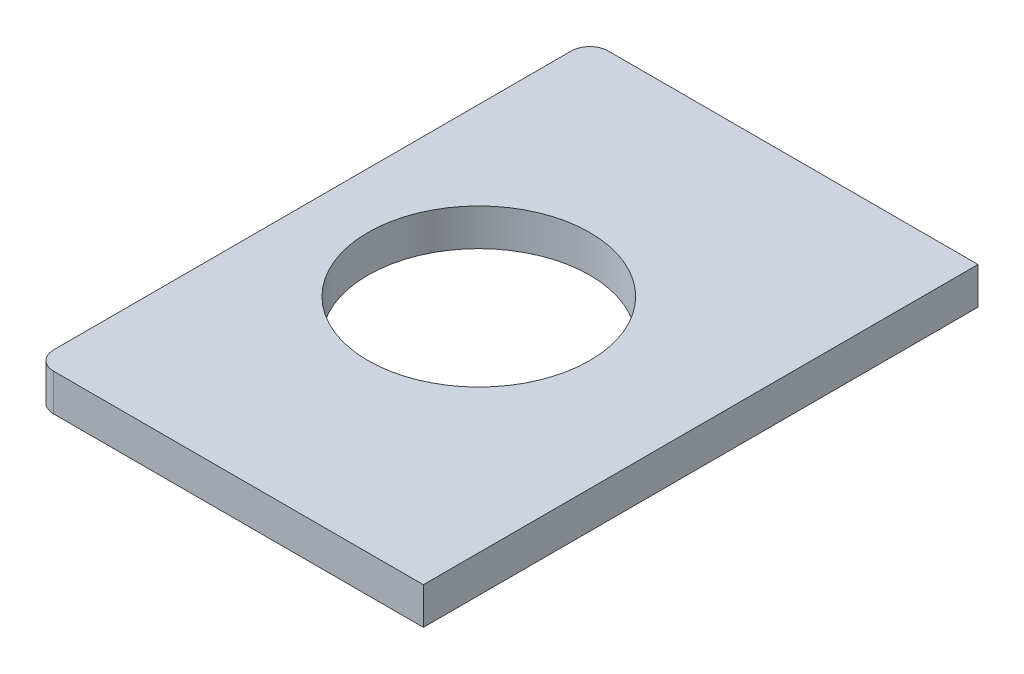
SolidWorks part; units mm, degrees
ref_plane "Front Plane" through (0, 0, 0) normal (0, 0, 1) x (1, 0, 0)
ref_plane "Top Plane" through (0, 0, 0) normal (0, 1, 0) x (1, 0, 0)
ref_plane "Right Plane" through (0, 0, 0) normal (1, 0, 0) x (0, 0, -1)
sketch "Sketch1" plane through (0, 0, 0) normal (0, 1, 0) x (1, 0, 0)
  line L1 (0, -15) -> (-10.5, -15)
  line L2 (-10.5, -15) -> (-10.5, 15)
  line L3 (-10.5, 15) -> (10.5, 15)
  line L4 (10.5, 15) -> (10.5, -15)
  line L5 (10.5, -15) -> (0, -15)
extrude "Boss-Extrude1" add sketch "Sketch1" along normal blind 2
fillet "Fillet1" radius 1 2 edges at (-10.5, 1, 15) (-10.5, 1, -15)
sketch "Sketch2" plane through (0, 2, 0) normal (0, 1, 0) x (1, 0, 0)
  circle A0 centre (-1.5, 0) radius 6
extrude "Cut-Extrude1" cut sketch "Sketch2" against normal through all
